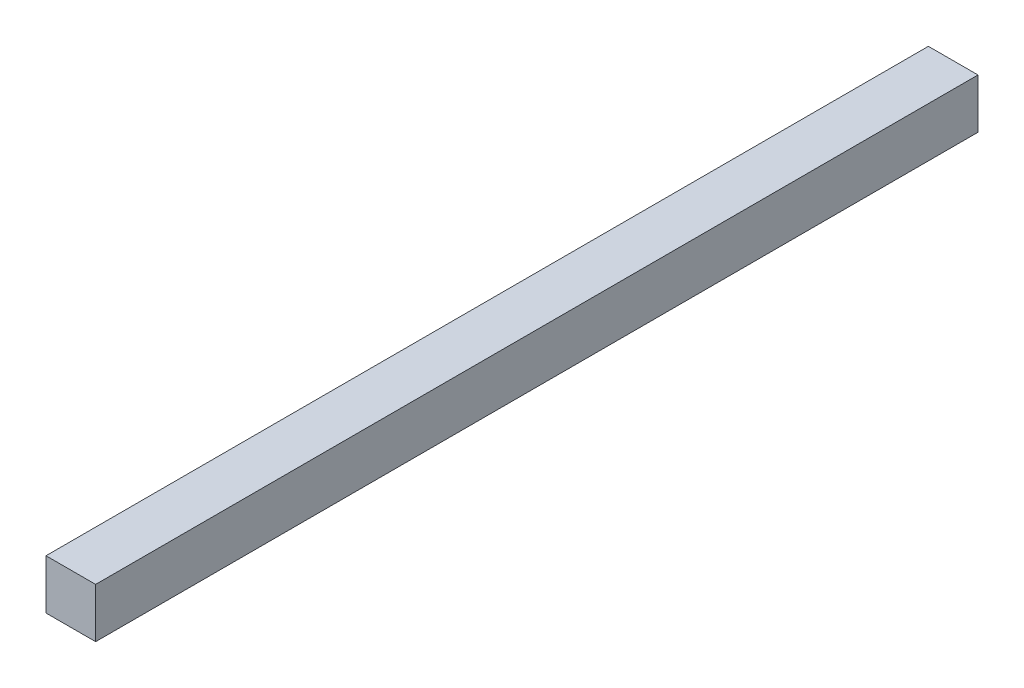
SolidWorks part; units mm, degrees
ref_plane "Front Plane" through (0, 0, 0) normal (0, 0, 1) x (1, 0, 0)
ref_plane "Top Plane" through (0, 0, 0) normal (0, 1, 0) x (1, 0, 0)
ref_plane "Right Plane" through (0, 0, 0) normal (1, 0, 0) x (0, 0, -1)
sketch "Sketch1" plane through (0, 0, 0) normal (0, 0, 1) x (1, 0, 0)
  line L1 (-10, -10) -> (10, -10)
  line L2 (-10, -10) -> (-10, 10)
  line L3 (-10, 10) -> (10, 10)
  line L4 (10, -10) -> (10, 10)
  line L5 (-10, -10) -> (10, 10) construction
  line L6 (-10, 10) -> (10, -10) construction
  point P0 (0, 0)
  dimension "D1" = 20
  dimension "D2" = 20
extrude "Boss-Extrude1" add sketch "Sketch1" along normal blind 355.6
sketch "Sketch2" plane through (-10, 0, 0) normal (-1, 0, 0) x (0, 0, 1)
  line L0 (304.8, 10) -> (304.8, -10)
  line L1 (355.6, 10) -> (0, 10) construction
  line L2 (355.6, -10) -> (0, -10) construction
  line L3 (355.6, 10) -> (355.6, -10) construction
  dimension "D1" = 50.8
